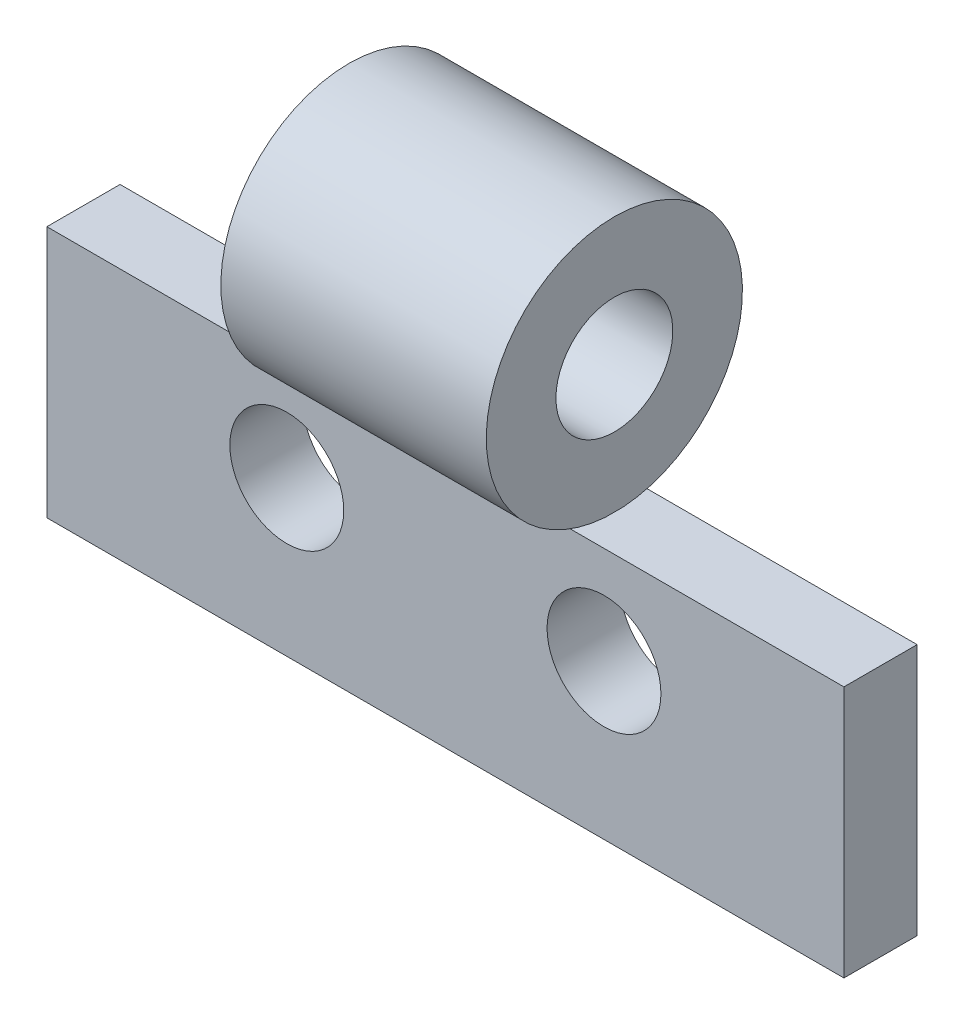
SolidWorks part; units mm, degrees
ref_plane "Front Plane" through (0, 0, 0) normal (0, 0, 1) x (1, 0, 0)
ref_plane "Top Plane" through (0, 0, 0) normal (0, 1, 0) x (1, 0, 0)
ref_plane "Right Plane" through (0, 0, 0) normal (1, 0, 0) x (0, 0, -1)
sketch "Sketch1" plane through (0, 0, 0) normal (0, 0, 1) x (1, 0, 0)
  line L1 (-24.278, 7.5938) -> (0.614, 7.5938)
  line L2 (-24.278, 7.5938) -> (-24.278, -0.2802)
  line L3 (-24.278, -0.2802) -> (0.614, -0.2802)
  line L4 (0.614, 7.5938) -> (0.614, -0.2802)
  dimension "D1" = 24.892
  dimension "D2" = 7.874
extrude "Boss-Extrude1" add sketch "Sketch1" along normal blind 2.286 contours L1 L4 L3 L2
sketch "Sketch4" plane through (-24.278, 0, 0) normal (-1, 0, 0) x (0, 0, 1)
  line L0 (1.143, 7.5938) -> (1.143, 11.5838) construction
  line L1 (2.286, 7.5938) -> (0, 7.5938) construction
  circle A0 centre (1.143, 11.5838) radius 4
  dimension "D1" = 8
  dimension "D2" = 3.99
extrude "Boss-Extrude3" add sketch "Sketch4" against normal blind 16.58
sketch "Sketch5" plane through (-24.278, 0, 0) normal (-1, 0, 0) x (0, 0, 1)
  circle A0 centre (1.143, 11.5838) radius 1.825
  dimension "D1" = 3.65
extrude "Cut-Extrude2" cut sketch "Sketch5" against normal blind 16.58
sketch "Sketch7" plane through (-24.278, 0, 0) normal (-1, 0, 0) x (0, 0, 1)
  line L0 (0.4302, 7.5938) -> (-5.5806, 7.5938)
  line L1 (0.8603, 7.5938) -> (0, 7.5938) construction
  line L2 (-5.5806, 7.5938) -> (-5.5806, 19.624)
  line L3 (-5.5806, 19.624) -> (9.5708, 19.624)
  line L4 (9.5708, 19.624) -> (9.5708, 7.5938)
  line L5 (9.5708, 7.5938) -> (0.4302, 7.5938)
extrude "Cut-Extrude3" cut sketch "Sketch7" against normal blind 8.29 contours L3 L4 L5 L0 L2
sketch "Sketch8" plane through (0, 0, 0) normal (0, 0, -1) x (-1, 0, 0)
  circle A0 centre (6.879, 4.5458) radius 1.778
  circle A1 centre (16.785, 4.5458) radius 1.778
  point P7 (11.832, 4.5458)
  dimension "D3" = 3.556
  dimension "D4" = 3.556
  dimension "D2" = 9.906
extrude "Cut-Extrude4" cut sketch "Sketch8" against normal blind 8.29 contours A0 | A1
sketch "Sketch9" plane through (-24.278, 0, 0) normal (-1, 0, 0) x (0, 0, 1)
  line L1 (2.286, 7.2606) -> (4.477, 7.2606)
  line L2 (2.286, 7.2606) -> (2.286, 8.5705)
  line L3 (2.286, 8.5705) -> (4.477, 8.5705)
  line L4 (4.477, 7.2606) -> (4.477, 8.5705)
  line L5 (0, 7.2606) -> (-1.7817, 7.2606)
  line L6 (0, 7.2606) -> (0, 8.0639)
  line L7 (0, 8.0639) -> (-1.7817, 8.0639)
  line L8 (-1.7817, 7.2606) -> (-1.7817, 8.0639)
extrude "Cut-Extrude5" cut sketch "Sketch9" against normal up to surface (8.29 mm away)
